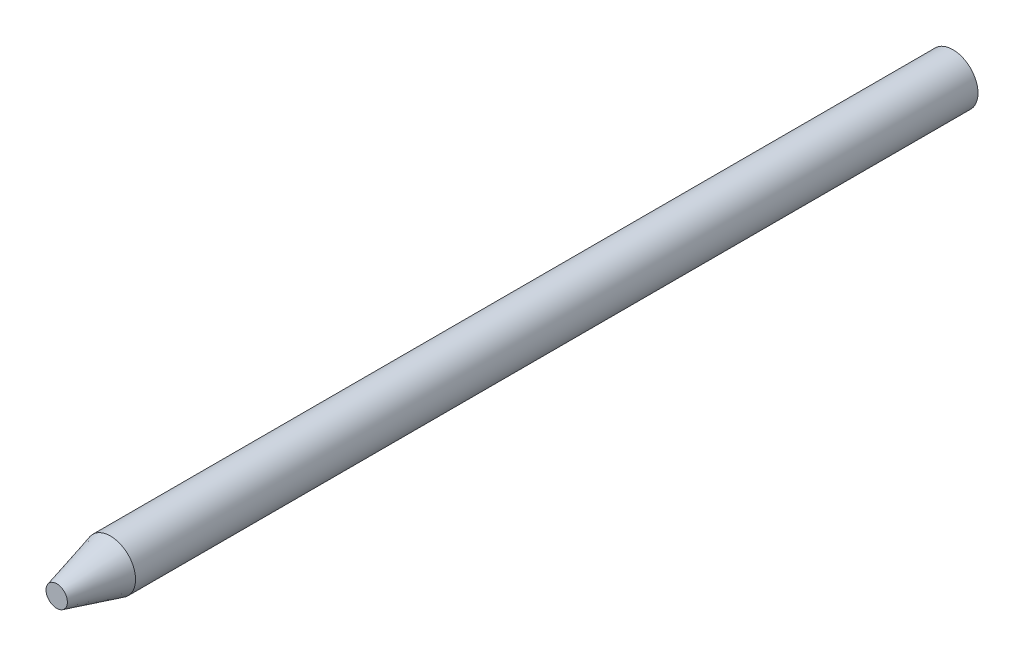
SolidWorks part; units mm, degrees
ref_plane "Front Plane" through (0, 0, 0) normal (0, 0, 1) x (1, 0, 0)
ref_plane "Top Plane" through (0, 0, 0) normal (0, 1, 0) x (1, 0, 0)
ref_plane "Right Plane" through (0, 0, 0) normal (1, 0, 0) x (0, 0, -1)
sketch "Sketch1" plane through (0, 0, 0) normal (0, 0, 1) x (1, 0, 0)
  circle A0 centre (0, 0) radius 1.778
  dimension "D1" = 3.556
extrude "Boss-Extrude1" add sketch "Sketch1" along normal blind 63.5
chamfer "Chamfer1" distance 3.81 angle 15 1 edges at (1.778, 0, 63.5)
